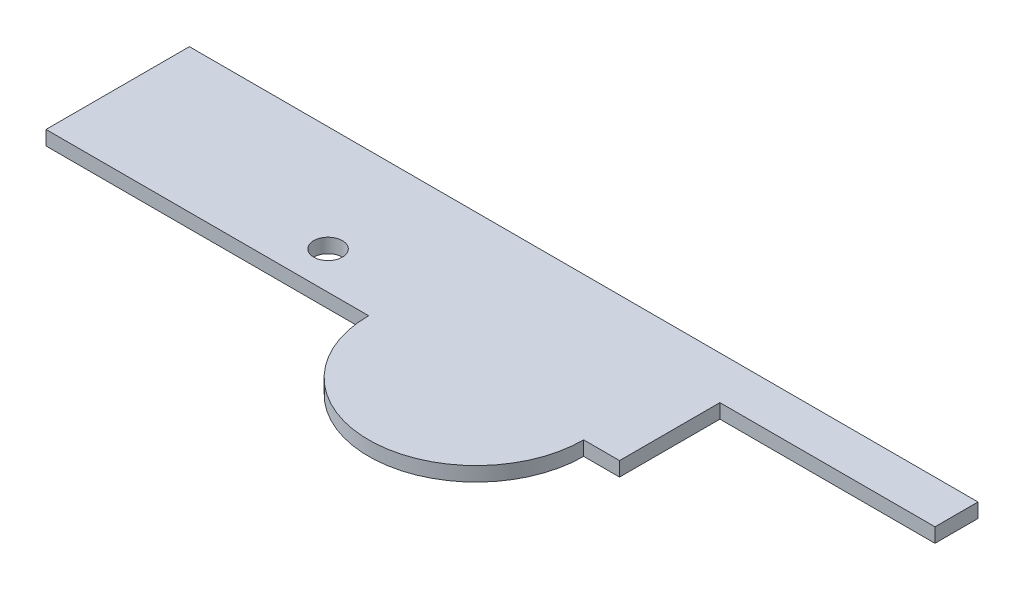
SolidWorks part; units mm, degrees
material "AISI 1020"
ref_plane "Front Plane" through (0, 0, 0) normal (0, 0, 1) x (1, 0, 0)
ref_plane "Top Plane" through (0, 0, 0) normal (0, 1, 0) x (1, 0, 0)
ref_plane "Right Plane" through (0, 0, 0) normal (1, 0, 0) x (0, 0, -1)
sketch "Sketch3" plane through (0, 0, 0) normal (0, 1, 0) x (1, 0, 0)
  line L6 (24.0323, -5) -> (26.5323, -5)
  line L7 (9.0323, -5) -> (-13.4677, -5)
  line L9 (-13.4677, -5) -> (-13.4677, 5)
  line L11 (-13.4677, 5) -> (26.5323, 5)
  line L16 (26.5323, -5) -> (26.5323, 2)
  line L17 (26.5323, 5) -> (41.5323, 5)
  line L18 (41.5323, 5) -> (41.5323, 2)
  line L19 (41.5323, 2) -> (26.5323, 2)
  arc A1 (9.0323, -5) -> (24.0323, -5) centre (16.5323, -5) ccw
  point P0 (0, 0)
  dimension "D3" = 15
  dimension "D1" = 7.5
  dimension "D2" = 15
  dimension "D4" = 30
  dimension "D5" = 40
  dimension "D6" = 10
  dimension "D7" = 3
extrude "Boss-Extrude6" add sketch "Sketch3" along normal blind 1
sketch "Sketch7" plane through (0, 0, 0) normal (0, -1, 0) x (1, 0, 0)
  line L2 (41.5323, -5) -> (-13.4677, -5) construction
  circle A1 centre (3.5823, 2.38) radius 1
  dimension "D4" = 2
  dimension "D7" = 7.38
extrude "Cut-Extrude1" cut sketch "Sketch7" against normal blind 10
